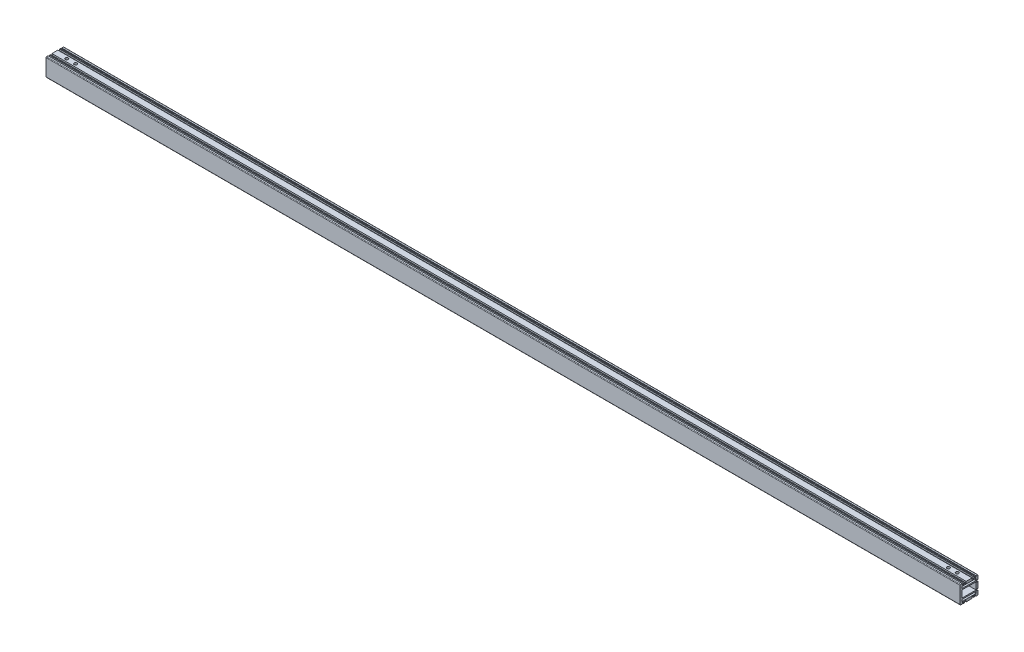
SolidWorks part; units mm, degrees
ref_plane "前视基准面" through (0, 0, 0) normal (0, 0, 1) x (1, 0, 0)
ref_plane "上视基准面" through (0, 0, 0) normal (0, 1, 0) x (1, 0, 0)
ref_plane "右视基准面" through (0, 0, 0) normal (1, 0, 0) x (0, 0, -1)
sketch "草图1" plane through (0, 0, 0) normal (1, 0, 0) x (0, 0, -1)
  line L0 (-15, 15) -> (15, -15) construction
  line L1 (-14, 15) -> (-11.5, 15)
  line L2 (-15, 14) -> (-15, -14)
  line L3 (-14, -15) -> (-11.5, -15)
  line L4 (15, 14) -> (15, 8)
  line L5 (15, 15) -> (-15, -15) construction
  line L6 (-11.5, 15) -> (-11.5, 13.5)
  line L7 (-11.5, 13.5) -> (-11.4, 13.5)
  line L8 (-11, 13.1) -> (-11, 12)
  line L9 (-11, 12) -> (-9.5, 12)
  line L10 (-9.5, 12) -> (-9.5, 15)
  line L11 (-9.5, 15) -> (-8, 15)
  line L12 (-8, 15) -> (-8, 12.5)
  line L13 (-8, 12.5) -> (-5, 12.5)
  line L14 (-5, 12.5) -> (-5, 15)
  line L15 (-5, 15) -> (5, 15)
  line L16 (0, 21.5201) -> (0, -18.309) construction
  line L17 (0, 55) -> (0, -55) construction
  line L18 (5, 12.5) -> (5, 15)
  line L19 (8, 12.5) -> (5, 12.5)
  line L20 (8, 15) -> (8, 12.5)
  line L21 (9.5, 15) -> (8, 15)
  line L22 (9.5, 12) -> (9.5, 15)
  line L23 (11, 12) -> (9.5, 12)
  line L24 (11, 13.1) -> (11, 12)
  line L25 (11.5, 13.5) -> (11.4, 13.5)
  line L26 (11.5, 15) -> (11.5, 13.5)
  line L27 (8, 15) -> (9.5, 15)
  line L28 (11.5, 15) -> (14, 15)
  line L29 (-19.8303, 0) -> (22.13, 0) construction
  line L30 (55, 0) -> (-55, 0) construction
  line L31 (8, -15) -> (9.5, -15)
  line L32 (11.5, -15) -> (11.5, -13.5)
  line L33 (11.5, -13.5) -> (11.4, -13.5)
  line L34 (11, -13.1) -> (11, -12)
  line L35 (11, -12) -> (9.5, -12)
  line L36 (9.5, -12) -> (9.5, -15)
  line L37 (9.5, -15) -> (8, -15)
  line L38 (8, -15) -> (8, -12.5)
  line L39 (8, -12.5) -> (5, -12.5)
  line L40 (5, -12.5) -> (5, -15)
  line L41 (-5, -15) -> (5, -15)
  line L42 (-5, -12.5) -> (-5, -15)
  line L43 (-8, -12.5) -> (-5, -12.5)
  line L44 (-8, -15) -> (-8, -12.5)
  line L45 (-9.5, -15) -> (-8, -15)
  line L46 (-9.5, -12) -> (-9.5, -15)
  line L47 (-11, -12) -> (-9.5, -12)
  line L48 (-11, -13.1) -> (-11, -12)
  line L49 (-11.5, -13.5) -> (-11.4, -13.5)
  line L50 (-11.5, -15) -> (-11.5, -13.5)
  line L51 (-9.5, -15) -> (-8, -15)
  line L52 (-5, -15) -> (5, -15)
  line L53 (8, -15) -> (9.5, -15)
  line L54 (11.5, -15) -> (14, -15)
  line L55 (15, 8) -> (12.5, 8)
  line L56 (12.5, 8) -> (12.5, 5)
  line L57 (12.5, 5) -> (15, 5)
  line L58 (12.5, -5) -> (15, -5)
  line L59 (12.5, -8) -> (12.5, -5)
  line L60 (15, -8) -> (12.5, -8)
  line L61 (15, 5) -> (15, -5)
  line L62 (15, -8) -> (15, -14)
  line L63 (12, -10.5) -> (12, -8.5)
  line L64 (-11.5, 11) -> (11.5, 11)
  line L65 (-12, 10.5) -> (-12, 8.5)
  line L66 (-11.5, 8) -> (11.5, 8)
  line L67 (12, 10.5) -> (12, 8.5)
  line L68 (-11.5, -8) -> (11.5, -8)
  line L69 (-12, -10.5) -> (-12, -8.5)
  line L70 (-11.5, -11) -> (11.5, -11)
  line L72 (-11.75, 6) -> (11.75, 6)
  line L73 (-11.75, 6) -> (-11.75, -6)
  line L74 (-11.75, -6) -> (11.75, -6)
  line L75 (11.75, 6) -> (11.75, -6)
  arc A0 (12, 8.5) -> (11.5, 8) centre (11.5, 8.5) cw
  arc A1 (11.5, 11) -> (12, 10.5) centre (11.5, 10.5) cw
  arc A2 (-11.5, 11) -> (-12, 10.5) centre (-11.5, 10.5) ccw
  arc A3 (-11.5, 8) -> (-12, 8.5) centre (-11.5, 8.5) cw
  arc A4 (-11, -13.1) -> (-11.4, -13.5) centre (-11.4, -13.1) cw
  arc A5 (11.4, -13.5) -> (11, -13.1) centre (11.4, -13.1) cw
  arc A6 (11.4, 13.5) -> (11, 13.1) centre (11.4, 13.1) ccw
  arc A7 (-11, 13.1) -> (-11.4, 13.5) centre (-11.4, 13.1) ccw
  arc A8 (-11.5, -8) -> (-12, -8.5) centre (-11.5, -8.5) ccw
  arc A9 (-11.5, -11) -> (-12, -10.5) centre (-11.5, -10.5) cw
  arc A10 (11.5, -11) -> (12, -10.5) centre (11.5, -10.5) ccw
  arc A11 (12, -8.5) -> (11.5, -8) centre (11.5, -8.5) ccw
  arc A12 (14, 15) -> (15, 14) centre (14, 14) cw
  arc A13 (14, -15) -> (15, -14) centre (14, -14) ccw
  arc A14 (-15, -14) -> (-14, -15) centre (-14, -14) ccw
  arc A15 (-15, 14) -> (-14, 15) centre (-14, 14) cw
  point P69 (12, 11)
  point P72 (-12, 11)
  point P77 (-11, -13.5)
  point P80 (11, -13.5)
  point P83 (11, 13.5)
  point P86 (-11, 13.5)
  point P99 (-12, -11)
  point P100 (12, -11)
  dimension "D17" = 0.5
  dimension "D18" = 0.4
  dimension "D21" = 1
  dimension "D1" = 3.5
  dimension "D2" = 1.5
  dimension "D3" = 0.5
  dimension "D4" = 1.5
  dimension "D5" = 3
  dimension "D6" = 30
  dimension "D7" = 30
  dimension "D8" = 1.5
  dimension "D9" = 2.5
  dimension "D10" = 3
  dimension "D11" = 2.5
  dimension "D12" = 7
  dimension "D13" = 3
  dimension "D14" = 4
  dimension "D15" = 3
  dimension "D16" = 24
  dimension "D19" = 23.5
  dimension "D20" = 12
extrude "凸台-拉伸1" add sketch "草图1" along normal mid plane 1542 contours A15 L2 A14 L3 L50 L49 A4 L48 L47 L46 L45 L44 L43 L42 L41 L40 L39 L38 L31 L36 L35 L34 A5 L33 L32 L54 A13 L62 L60 L59 L58 L61 L57 L56 L55 L4 A12 L28 L26 L25 A6 L24 L23 L22 L21 L20 L19 L18 L15 L14 L13
hole_wizard "M6 螺纹孔1" positions "草图3" profile "草图2" tap size "M6" standard "GB"
sketch "草图3" plane through (0, 15, 0) normal (0, 1, 0) x (-1, 0, 0)
  line L0 (-771, 5) -> (-771, -5) construction
  line L1 (-771, 15) -> (771, 15) construction
  point P0 (-751, 0)
  point P1 (-736, 0)
  point P4 (736, 0)
  point P7 (751, 0)
  dimension "D1" = 20
  dimension "D2" = 15
sketch "草图2" plane through (751, 15, 0) normal (1, 0, 0) x (0, 0, 1)
  line L0 (0, 0) -> (0, 16.5022)
  line L1 (0, 16.5022) -> (2.5, 15)
  line L2 (2.5, 15) -> (2.5, 0)
  line L5 (2.5, 0) -> (0, 0)
  line L10 (0, 16.5022) -> (-2.5, 15) construction
  line L11 (0, -6.35) -> (0, 107.95) construction
  dimension "螺纹孔钻头直径" = 5
  dimension "螺纹孔钻头深度" = 15
  dimension "导头角度" = 118
cosmetic thread "孔螺蚊线1" parameters "D1"=9, "D2"=6
cosmetic thread "孔螺蚊线2" parameters "D1"=9, "D2"=6
cosmetic thread "孔螺蚊线3" parameters "D1"=9, "D2"=6
cosmetic thread "孔螺蚊线4" parameters "D1"=9, "D2"=6
hole_wizard "M6 螺纹孔2" positions "草图7" profile "草图6" tap size "M6" standard "GB"
sketch "草图7" plane through (0, 0, -15) normal (0, 0, -1) x (-1, 0, 0)
  line L0 (-771, 5) -> (-771, -5) construction
  line L1 (-771, 15) -> (771, 15) construction
  point P0 (-751, 0)
  point P1 (-736, 0)
  point P4 (736, 0)
  point P7 (751, 0)
  dimension "D1" = 20
  dimension "D2" = 15
sketch "草图6" plane through (751, 0, -15) normal (1, 0, 0) x (0, 1, 0)
  line L0 (0, 0) -> (0, 16.5022)
  line L1 (0, 16.5022) -> (2.5, 15)
  line L2 (2.5, 15) -> (2.5, 0)
  line L5 (2.5, 0) -> (0, 0)
  line L10 (0, 16.5022) -> (-2.5, 15) construction
  line L11 (0, -6.35) -> (0, 107.95) construction
  dimension "螺纹孔钻头直径" = 5
  dimension "螺纹孔钻头深度" = 15
  dimension "导头角度" = 118
cosmetic thread "孔螺蚊线5" parameters "D1"=3.25, "D2"=6
cosmetic thread "孔螺蚊线6" parameters "D1"=3.25, "D2"=6
cosmetic thread "孔螺蚊线7" parameters "D1"=3.25, "D2"=6
cosmetic thread "孔螺蚊线8" parameters "D1"=3.25, "D2"=6
hole_wizard "M6 螺纹孔3" positions "草图9" profile "草图8" tap size "M6" standard "GB"
sketch "草图9" plane through (0, -15, 0) normal (0, -1, 0) x (1, 0, 0)
  line L0 (771, 5) -> (771, -5) construction
  line L1 (771, 15) -> (-771, 15) construction
  point P0 (751, 0)
  point P1 (736, 0)
  point P4 (-736, 0)
  point P7 (-751, 0)
  dimension "D1" = 20
  dimension "D2" = 15
sketch "草图8" plane through (751, -15, 0) normal (1, 0, 0) x (0, 0, -1)
  line L0 (0, 0) -> (0, 16.5022)
  line L1 (0, 16.5022) -> (2.5, 15)
  line L2 (2.5, 15) -> (2.5, 0)
  line L5 (2.5, 0) -> (0, 0)
  line L10 (0, 16.5022) -> (-2.5, 15) construction
  line L11 (0, -6.35) -> (0, 107.95) construction
  dimension "螺纹孔钻头直径" = 5
  dimension "螺纹孔钻头深度" = 15
  dimension "导头角度" = 118
cosmetic thread "孔螺蚊线9" parameters "D1"=9, "D2"=6
cosmetic thread "孔螺蚊线10" parameters "D1"=9, "D2"=6
cosmetic thread "孔螺蚊线11" parameters "D1"=9, "D2"=6
cosmetic thread "孔螺蚊线12" parameters "D1"=9, "D2"=6
hole_wizard "M6 螺纹孔4" positions "草图11" profile "草图10" tap size "M6" standard "GB"
sketch "草图11" plane through (0, 0, -15) normal (0, 0, -1) x (-1, 0, 0)
  line L0 (-771, -15) -> (771, -15) construction
  line L1 (-771, -8) -> (-771, -14) construction
  line L2 (771, -8) -> (771, -14) construction
  point P0 (411, 0)
  point P1 (351, 0)
  point P3 (-411, 0)
  point P5 (-351, 0)
  dimension "D1" = 60
  dimension "D2" = 15
  dimension "D3" = 360
  dimension "D4" = 360
  dimension "D5" = 60
sketch "草图10" plane through (-411, 0, -15) normal (1, 0, 0) x (0, 1, 0)
  line L0 (0, 0) -> (0, 16.5022)
  line L1 (0, 16.5022) -> (2.5, 15)
  line L2 (2.5, 15) -> (2.5, 0)
  line L5 (2.5, 0) -> (0, 0)
  line L10 (0, 16.5022) -> (-2.5, 15) construction
  line L11 (0, -6.35) -> (0, 107.95) construction
  dimension "螺纹孔钻头直径" = 5
  dimension "螺纹孔钻头深度" = 15
  dimension "导头角度" = 118
cosmetic thread "孔螺蚊线13" parameters "D1"=3.25, "D2"=6
cosmetic thread "孔螺蚊线14" parameters "D1"=3.25, "D2"=6
cosmetic thread "孔螺蚊线15" parameters "D1"=3.25, "D2"=6
cosmetic thread "孔螺蚊线16" parameters "D1"=3.25, "D2"=6
